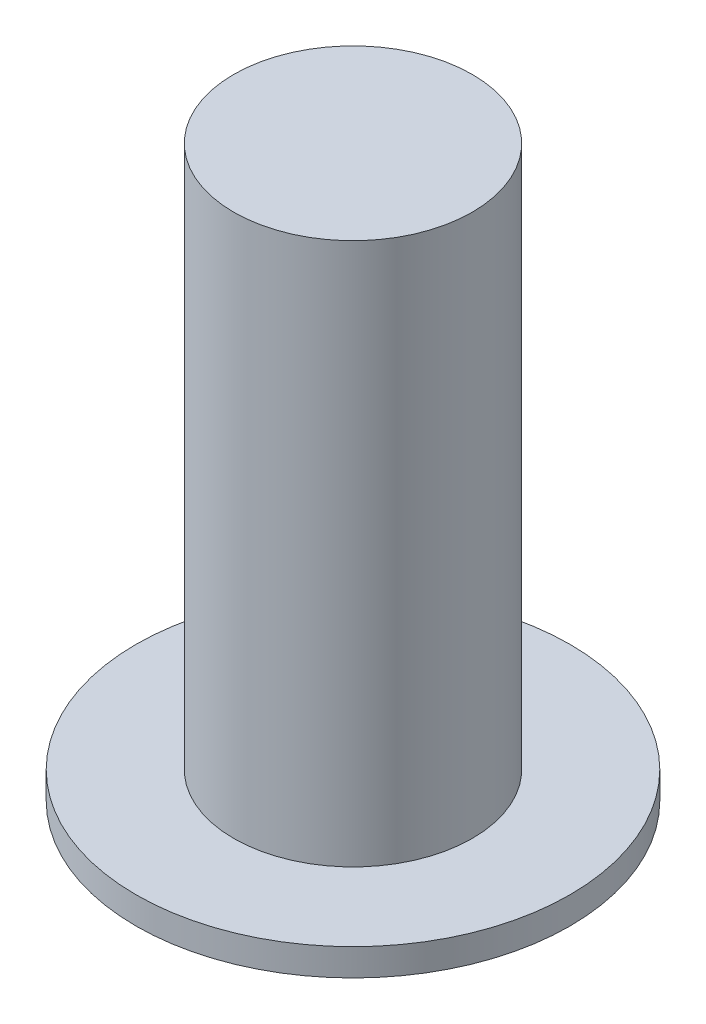
SolidWorks part; units mm, degrees
ref_plane "Front Plane" through (0, 0, 0) normal (0, 0, 1) x (1, 0, 0)
ref_plane "Top Plane" through (0, 0, 0) normal (0, 1, 0) x (1, 0, 0)
ref_plane "Right Plane" through (0, 0, 0) normal (1, 0, 0) x (0, 0, -1)
sketch "Sketch1" plane through (0, 0, 0) normal (0, 1, 0) x (1, 0, 0)
  circle A0 centre (0, 0) radius 22
  dimension "D1" = 44
extrude "Boss-Extrude1" add sketch "Sketch1" along normal blind 100 contours A0
sketch "Sketch2" plane through (0, 0, 0) normal (0, 1, 0) x (1, 0, 0)
  circle A2 centre (0, 0) radius 40
  dimension "D1" = 80
extrude "Boss-Extrude2" add sketch "Sketch2" against normal blind 5
